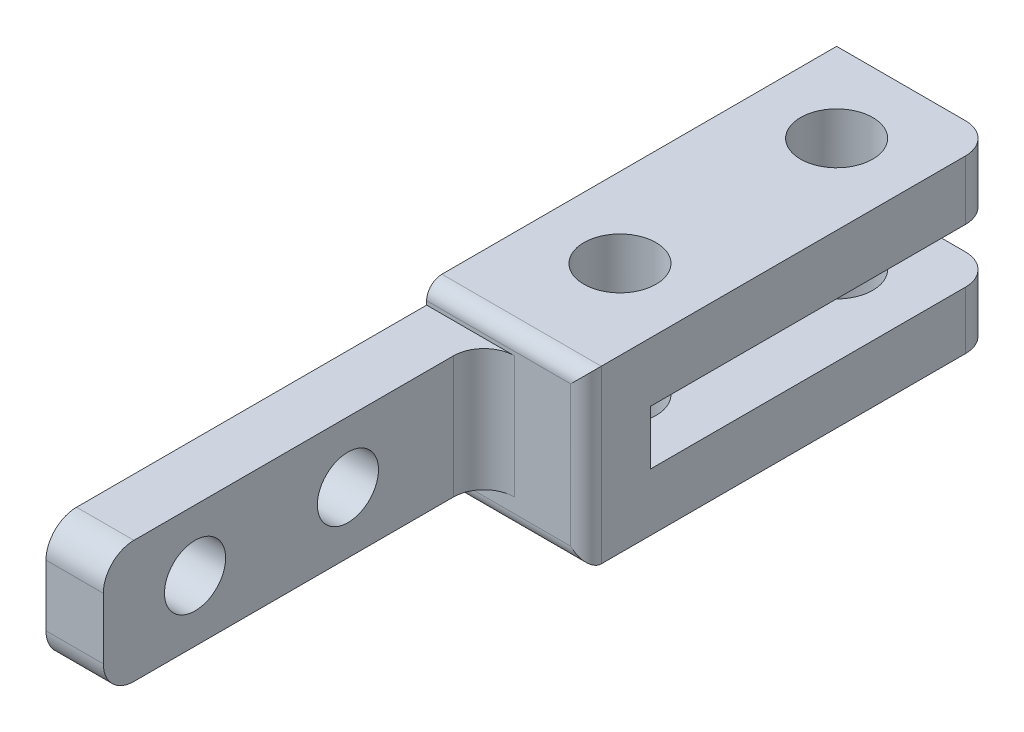
SolidWorks part; units mm, degrees
ref_plane "Front Plane" through (0, 0, 0) normal (0, 0, 1) x (1, 0, 0)
ref_plane "Top Plane" through (0, 0, 0) normal (0, 1, 0) x (1, 0, 0)
ref_plane "Right Plane" through (0, 0, 0) normal (1, 0, 0) x (0, 0, -1)
sketch "Sketch1" plane through (0, 0, 0) normal (0, 1, 0) x (1, 0, 0)
  line L1 (0, 0) -> (4.7625, 0)
  line L2 (0, 0) -> (0, -34.798)
  line L3 (0, -34.798) -> (4.7625, -34.798)
  line L4 (4.7625, 0) -> (4.7625, -34.798)
  dimension "D1" = 4.7625
  dimension "D2" = 34.798
extrude "Boss-Extrude1" add sketch "Sketch1" along normal blind 10.16
sketch "Sketch2" plane through (4.7625, 0, 0) normal (1, 0, 0) x (0, 0, -1)
  line L0 (-27.178, 5.08) -> (-34.798, 5.08) construction
  line L1 (-34.798, 10.16) -> (-34.798, 0) construction
  line L2 (-27.178, 5.08) -> (-27.178, 0) construction
  line L3 (-34.798, 0) -> (0, 0) construction
  line L4 (-27.178, 5.08) -> (-14.478, 5.08) construction
  circle A0 centre (-27.178, 5.08) radius 2.54
  circle A1 centre (-14.478, 5.08) radius 2.54
  dimension "D1" = 5.08
  dimension "D2" = 7.62
  dimension "D3" = 12.7
extrude "Cut-Extrude1" cut sketch "Sketch2" against normal through all
ref_plane "Plane1" through (0, 5.08, 0) normal (0, 1, 0) x (1, 0, 0)
sketch "Sketch3" plane through (0, 5.08, 0) normal (0, 1, 0) x (1, 0, 0)
  line L1 (0, -3.175) -> (13.2385, -3.175)
  line L3 (0, 30.8864) -> (13.2385, 30.8864)
  line L4 (13.2385, -3.175) -> (13.2385, 30.8864)
  line L5 (4.7625, 0) -> (0, 0) construction
  line L6 (0, 0) -> (0, -34.798) construction
  line L7 (4.7625, -34.798) -> (4.7625, 0) construction
  line L8 (0, 30.8864) -> (0, -3.175)
  line L9 (6.6192, 6.2662) -> (0, 6.2662) construction
  line L10 (6.6192, 6.2662) -> (13.2385, 6.2662) construction
  line L11 (6.6192, 24.2672) -> (13.2385, 24.2672) construction
  line L12 (6.6192, 24.2672) -> (0, 24.2672) construction
  line L13 (6.6192, 24.2672) -> (6.6192, 30.8864) construction
  line L14 (6.6192, 24.2672) -> (6.6192, 6.2662) construction
  circle A0 centre (6.6192, 6.2662) radius 2.9997
  circle A1 centre (6.6192, 24.2672) radius 2.9997
  dimension "D3" = 5.9995
  dimension "D1" = 1.8567
  dimension "D2" = 6.2662
  dimension "D4" = 18.001
  dimension "D5" = 3.175
extrude "Boss-Extrude2" add sketch "Sketch3" along normal blind 6.6675 and the other way blind 7.5565
sketch "Sketch5" plane through (0, 0, 34.798) normal (0, 0, 1) x (1, 0, 0)
  line L1 (0, 10.16) -> (4.7625, 10.16)
  line L2 (0, 10.16) -> (0, 0)
  line L3 (0, 0) -> (4.7625, 0)
  line L4 (4.7625, 10.16) -> (4.7625, 0)
sketch "Sketch6" plane through (0, 0, -30.8864) normal (0, 0, -1) x (-1, 0, 0)
  line L0 (0, 5.08) -> (-13.2385, 5.08) construction
  line L1 (0, 10.16) -> (0, 0) construction
  line L2 (-13.2385, -2.4765) -> (-13.2385, 11.7475) construction
  line L4 (0, 6.8174) -> (-13.2385, 6.8174)
  line L5 (0, 6.8174) -> (0, 2.3089)
  line L6 (0, 2.3089) -> (-13.2385, 2.3089)
  line L7 (-13.2385, 6.8174) -> (-13.2385, 2.3089)
  dimension "D1" = 2.7711
  dimension "D2" = 1.7374
extrude "Cut-Extrude3" cut sketch "Sketch6" against normal blind 28.702
sketch "Sketch7" plane through (13.2385, 0, 0) normal (1, 0, 0) x (0, 0, -1)
  line L0 (-3.175, 11.7475) -> (30.8864, 11.7475) construction
  line L1 (30.8864, -2.4765) -> (-3.175, -2.4765)
  line L2 (30.8864, -2.4765) -> (30.8864, 11.7475)
  line L3 (30.8864, 11.7475) -> (-3.175, 11.7475)
  line L4 (-3.175, -2.4765) -> (-3.175, 11.7475)
  line L6 (-3.175, -2.4765) -> (-3.175, 11.7475) construction
sketch "Sketch8" plane through (0, 0, 0) normal (-1, 0, 0) x (0, 0, 1)
  line L1 (-30.8864, 11.7475) -> (-2.1844, 11.7475)
  line L2 (-30.8864, 11.7475) -> (-30.8864, -2.4765)
  line L3 (-30.8864, -2.4765) -> (-2.1844, -2.4765)
  line L4 (-2.1844, 11.7475) -> (-2.1844, -2.4765)
  line L5 (-30.8864, -2.4765) -> (3.175, -2.4765) construction
  line L7 (-2.1844, 2.3089) -> (-2.1844, 6.8174) construction
fillet "Fillet1" radius 2.54 5 edges at (4.7625, 5.08, 3.175) (2.3813, 0, 34.798) (2.3813, 10.16, 34.798) (13.2385, -0.0838, -30.8864) (13.2385, 9.2824, -30.8864)
fillet "Fillet2" radius 1.27 3 edges at (6.6192, -2.4765, 3.175) (13.2385, 4.6355, 3.175) (6.6192, 11.7475, 3.175)
